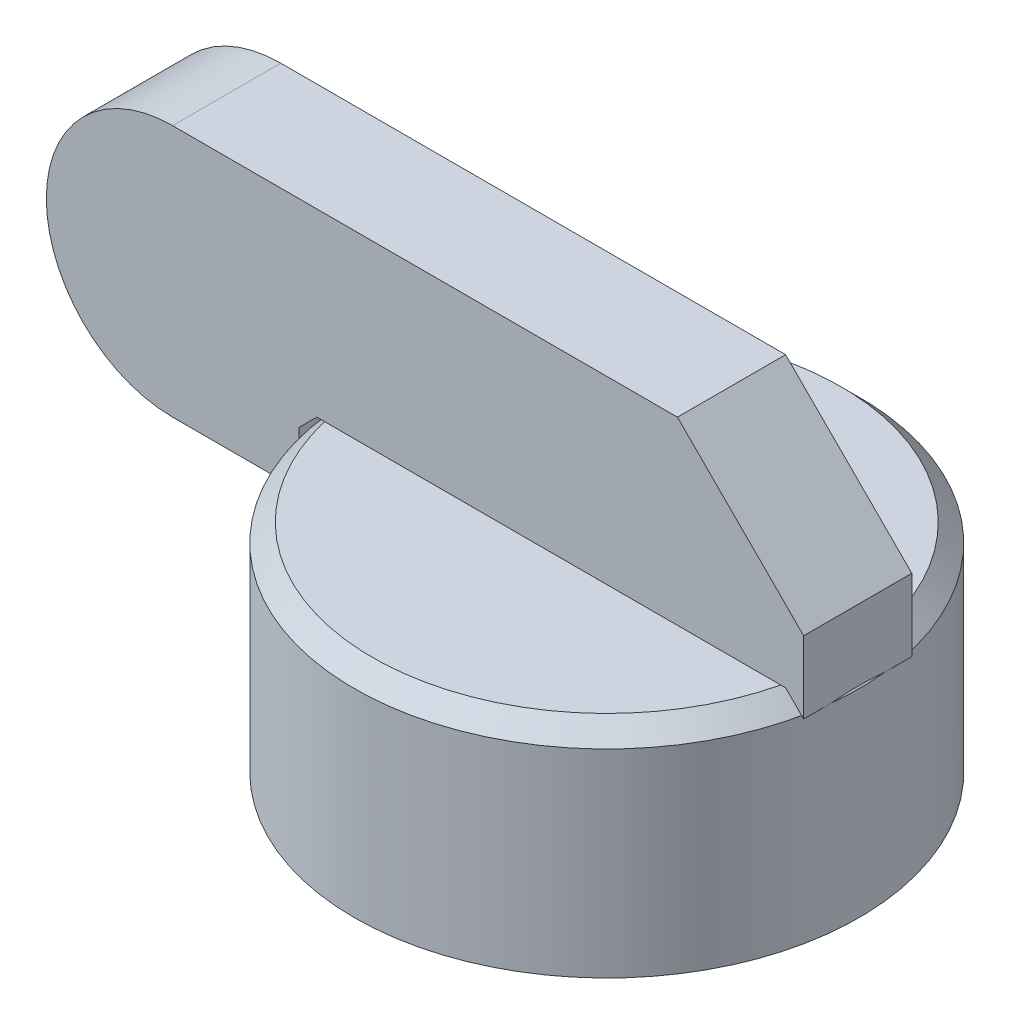
SolidWorks part; units mm, degrees
ref_plane "Front Plane" through (0, 0, 0) normal (0, 0, 1) x (1, 0, 0)
ref_plane "Top Plane" through (0, 0, 0) normal (0, 1, 0) x (1, 0, 0)
ref_plane "Right Plane" through (0, 0, 0) normal (1, 0, 0) x (0, 0, -1)
sketch "Sketch1" plane through (0, 0, 0) normal (0, 1, 0) x (1, 0, 0)
  circle A0 centre (0, 0) radius 11.1125
  dimension "D1" = 22.225
extrude "Boss-Extrude1" add sketch "Sketch1" along normal blind 9.525 contours A0
chamfer "Chamfer1" distance 0.7937 angle 45 1 edges at (0, 9.525, 11.1125)
sketch "Sketch2" plane through (0, 0, 0) normal (0, 0, 1) x (1, 0, 0)
  line L10 (11.049, 8.7313) -> (11.049, 11.9063)
  line L11 (11.049, 11.9063) -> (5.4927, 17.4625)
  line L12 (5.4927, 17.4625) -> (-16.7323, 17.4625)
  line L13 (-16.7323, 6.35) -> (-11.176, 6.35)
  line L15 (-11.176, 6.35) -> (-11.176, 8.7313)
  line L16 (-11.176, 8.7313) -> (-10.3823, 9.525)
  line L17 (-10.3823, 9.525) -> (10.2552, 9.525)
  line L18 (10.2552, 9.525) -> (11.049, 8.7313)
  arc A1 (-16.7323, 17.4625) -> (-16.7323, 6.35) centre (-16.7323, 11.9062) ccw
  point P0 (-0.0635, 9.525)
  point P1 (0, 0)
  point P20 (-22.2885, 11.9062)
  dimension "D2" = 9.525
  dimension "D3" = 11.176
  dimension "D11" = 33.3375
  dimension "D12" = 11.1125
  dimension "D13" = 3.175
  dimension "D14" = 3.175
  dimension "D15" = 2.3813
  dimension "D16" = 20.6375
  dimension "D17" = 45
  dimension "D18" = 5.5563
extrude "Boss-Extrude30" add sketch "Sketch2" along normal mid plane 4.7625
